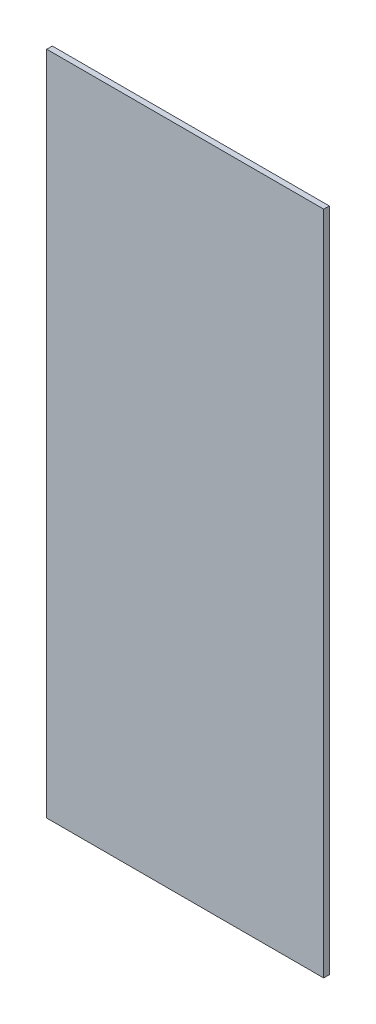
SolidWorks part; units mm, degrees
material "ABS"
ref_plane "X-Y Datum" through (0, 0, 0) normal (0, 0, 1) x (1, 0, 0)
ref_plane "X-Z Datum" through (0, 0, 0) normal (0, 1, 0) x (1, 0, 0)
ref_plane "Y-Z Datum" through (0, 0, 0) normal (1, 0, 0) x (0, 0, -1)
sketch "Sketch1" plane through (0, 0, 0) normal (0, 0, 1) x (1, 0, 0)
  line L1 (-75.4476, 204.1965) -> (-154.3351, 204.1965)
  line L2 (-75.4476, 204.1965) -> (-75.4476, 14.5405)
  line L3 (-75.4476, 14.5405) -> (-154.3351, 14.5405)
  line L4 (-154.3351, 204.1965) -> (-154.3351, 14.5405)
extrude "Boss-Extrude1" add sketch "Sketch1" along normal blind 1.5875
